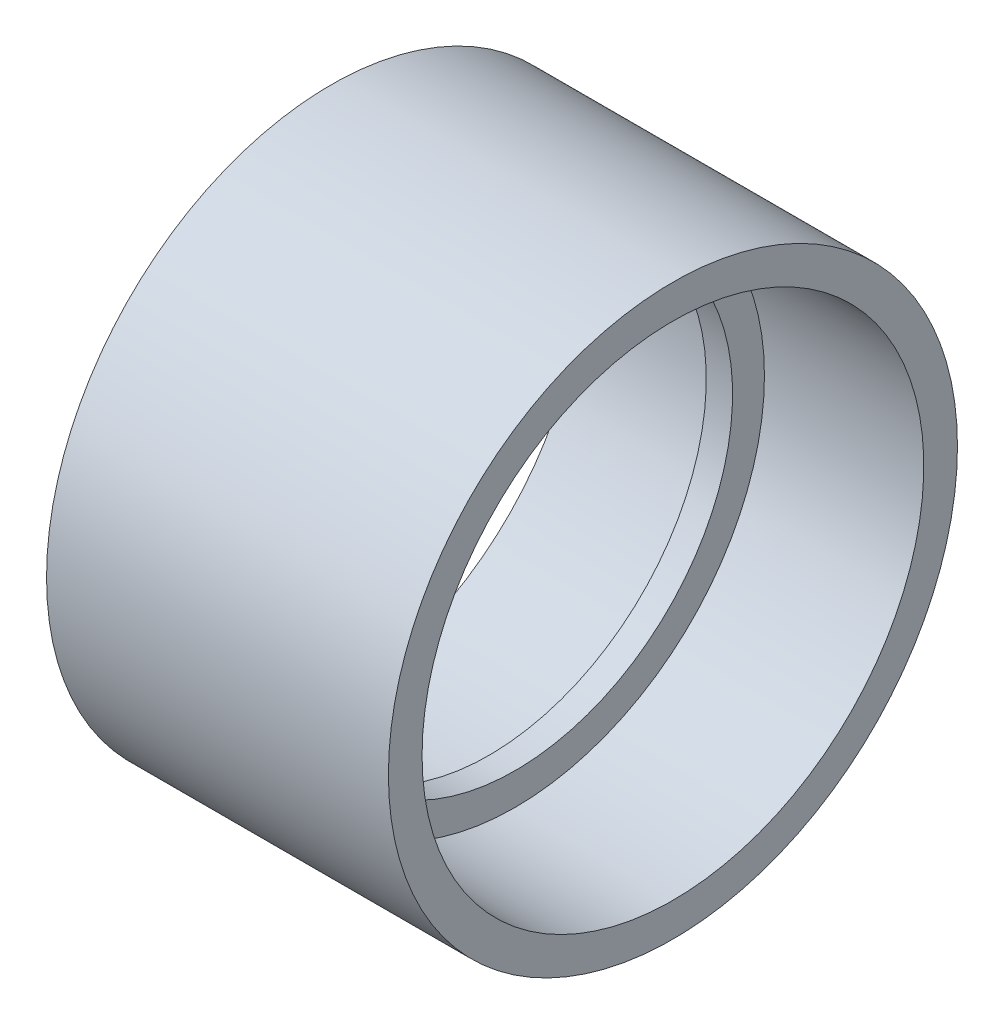
SolidWorks part; units mm, degrees
material "ABS"
ref_plane "Front Plane" through (0, 0, 0) normal (0, 0, 1) x (1, 0, 0)
ref_plane "Top Plane" through (0, 0, 0) normal (0, 1, 0) x (1, 0, 0)
ref_plane "Right Plane" through (0, 0, 0) normal (1, 0, 0) x (0, 0, -1)
sketch "Sketch0" plane through (0, 0, 0) normal (0, 0, 1) x (1, 0, 0)
  line L0 (-20.6375, 0) -> (0, 0) construction
  line L1 (0, 0) -> (0, 34.3535) construction
  line L2 (-1.5875, 0) -> (0, 0) construction
  line L4 (-20.6375, 34.3535) -> (-20.6375, -34.3535) construction
  line L5 (-1.5875, 30.099) -> (-20.6375, 30.2895) construction
  line L6 (-1.5875, 30.099) -> (-1.5875, -30.099) construction
  line L7 (-1.5875, -30.099) -> (-20.6375, -30.2895) construction
  line L8 (-20.6375, 30.2895) -> (-20.6375, -30.2895) construction
  line L14 (-1.5875, 26.2509) -> (-1.5875, -26.2509) construction
  line L15 (-1.5875, -26.2509) -> (-1.5875, -30.3149) construction
  line L16 (-20.6375, -30.2895) -> (-20.6375, -34.3535) construction
  line L21 (-20.6375, 0) -> (-1.5875, 0) construction
  dimension "A" = 3.175
  dimension "OD A" = 60.579
  dimension "OD B" = 60.198
  dimension "ID" = 52.5018
  dimension "H" = 4.064
  dimension "C" = 19.05
sketch "Sketch1" plane through (0, 0, 0) normal (0, 0, 1) x (1, 0, 0)
  line L0 (-20.6375, 0) -> (0, 0) construction
  line L1 (-20.6375, 0) -> (0, 0) construction
  line L2 (-20.6375, -34.3535) -> (20.6375, -34.3535)
  line L3 (0, 0) -> (0, -34.3535) construction
  line L4 (-20.6375, -34.3535) -> (-20.6375, -30.2895)
  line L5 (-20.6375, -30.2895) -> (-1.5875, -30.099)
  line L6 (-1.5875, -34.3535) -> (-1.5875, -30.099) construction
  line L7 (1.5875, -26.2509) -> (1.5875, -30.099)
  line L8 (-1.5875, -26.2509) -> (-1.5875, -30.099)
  line L9 (20.6375, -30.2895) -> (1.5875, -30.099)
  line L10 (20.6375, -34.3535) -> (20.6375, -30.2895)
  line L11 (-1.5875, -26.2509) -> (1.5875, -26.2509)
revolve "Revolve1" add sketch "Sketch1" angle 360 about L1
sketch "Sketch2" plane through (-1.5875, 0, 0) normal (-1, 0, 0) x (0, 0, 1)
  circle A0 centre (0, 0) radius 30.099 construction
  circle A1 centre (0, 0) radius 30.099
extrude "Cut-Extrude1" [suppressed] cut sketch "Sketch2" against normal up to surface (3.175 mm away)
